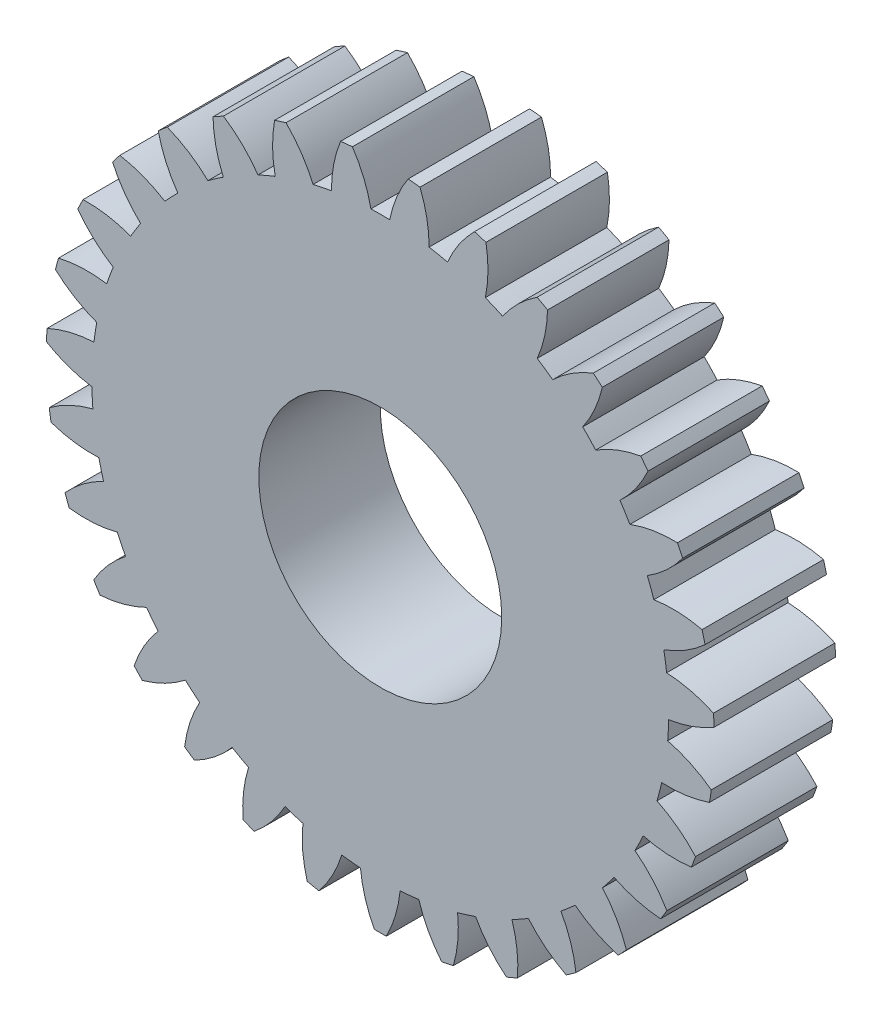
SolidWorks part; units mm, degrees
ref_plane "前视基准面" through (0, 0, 0) normal (0, 0, 1) x (1, 0, 0)
ref_plane "上视基准面" through (0, 0, 0) normal (0, 1, 0) x (1, 0, 0)
ref_plane "右视基准面" through (0, 0, 0) normal (1, 0, 0) x (0, 0, -1)
sketch "草图1" plane through (0, 0, 0) normal (0, 0, 1) x (1, 0, 0)
  circle A0 centre (0, 0) radius 3 construction
  circle A1 centre (0, 0) radius 3
  arc A124 (7.1228, -0.129) -> (8.2456, 0.2706) centre (6.6642, 2.9369) ccw
  arc A125 (8.2456, 0.2706) -> (8.2306, 0.565) centre (0, 0) ccw
  arc A126 (8.2306, 0.565) -> (7.0732, 0.8489) centre (6.9271, -2.2477) ccw
  arc A127 (7.0732, 0.8489) -> (7.003, 1.3075) centre (0, 0) ccw
  arc A128 (7.003, 1.3075) -> (8.0223, 1.9249) centre (5.9365, 4.2183) ccw
  arc A129 (8.0223, 1.9249) -> (7.9484, 2.2102) centre (0, 0) ccw
  arc A130 (7.9484, 2.2102) -> (6.7576, 2.2554) centre (7.2377, -0.8072) ccw
  arc A131 (6.7576, 2.2554) -> (6.5964, 2.6904) centre (0, 0) ccw
  arc A132 (6.5964, 2.6904) -> (7.4706, 3.5004) centre (4.9659, 5.327) ccw
  arc A133 (7.4706, 3.5004) -> (7.3408, 3.765) centre (0, 0) ccw
  arc A134 (7.3408, 3.765) -> (6.1652, 3.5695) centre (7.2521, 0.6662) ccw
  arc A135 (6.1652, 3.5695) -> (5.9198, 3.9632) centre (0, 0) ccw
  arc A136 (5.9198, 3.9632) -> (6.6131, 4.9325) centre (3.7919, 6.2175) ccw
  arc A137 (6.6131, 4.9325) -> (6.4327, 5.1656) centre (0, 0) ccw
  arc A138 (6.4327, 5.1656) -> (5.3205, 4.7375) centre (6.9695, 2.1124) ccw
  arc A139 (5.3205, 4.7375) -> (5.0009, 5.0737) centre (0, 0) ccw
  arc A140 (5.0009, 5.0737) -> (5.4848, 6.1628) centre (2.4627, 6.8536) ccw
  arc A141 (5.4848, 6.1628) -> (5.2612, 6.3547) centre (0, 0) ccw
  arc A142 (5.2612, 6.3547) -> (4.258, 5.7115) centre (6.4016, 3.4721) ccw
  arc A143 (4.258, 5.7115) -> (3.8772, 5.9765) centre (0, 0) ccw
  arc A144 (3.8772, 5.9765) -> (4.1319, 7.1407) centre (1.0327, 7.209) ccw
  arc A145 (4.1319, 7.1407) -> (3.8743, 7.2837) centre (0, 0) ccw
  arc A146 (3.8743, 7.2837) -> (3.0211, 6.4517) centre (5.5716, 4.6897) ccw
  arc A147 (3.0211, 6.4517) -> (2.5947, 6.6347) centre (0, 0) ccw
  arc A148 (2.5947, 6.6347) -> (2.6099, 7.8263) centre (-0.4396, 7.2693) ccw
  arc A149 (2.6099, 7.8263) -> (2.3288, 7.9145) centre (0, 0) ccw
  arc A150 (2.3288, 7.9145) -> (1.6605, 6.9278) centre (4.5136, 5.7153) ccw
  arc A151 (1.6605, 6.9278) -> (1.2061, 7.0212) centre (0, 0) ccw
  arc A152 (1.2061, 7.0212) -> (0.9811, 8.1915) centre (-1.8939, 7.032) ccw
  arc A153 (0.9811, 8.1915) -> (0.6879, 8.2213) centre (0, 0) ccw
  arc A154 (0.6879, 8.2213) -> (0.232, 7.1202) centre (3.2707, 6.5069) ccw
  arc A155 (0.232, 7.1202) -> (-0.232, 7.1202) centre (0, 0) ccw
  arc A156 (-0.232, 7.1202) -> (-0.6879, 8.2213) centre (-3.2707, 6.5069) ccw
  arc A157 (-0.6879, 8.2213) -> (-0.9811, 8.1915) centre (0, 0) ccw
  arc A158 (-0.9811, 8.1915) -> (-1.2061, 7.0212) centre (1.8939, 7.032) ccw
  arc A159 (-1.2061, 7.0212) -> (-1.6605, 6.9278) centre (0, 0) ccw
  arc A160 (-1.6605, 6.9278) -> (-2.3288, 7.9145) centre (-4.5136, 5.7153) ccw
  arc A161 (-2.3288, 7.9145) -> (-2.6099, 7.8263) centre (0, 0) ccw
  arc A162 (-2.6099, 7.8263) -> (-2.5947, 6.6347) centre (0.4396, 7.2693) ccw
  arc A163 (-2.5947, 6.6347) -> (-3.0211, 6.4517) centre (0, 0) ccw
  arc A164 (-3.0211, 6.4517) -> (-3.8743, 7.2837) centre (-5.5716, 4.6897) ccw
  arc A165 (-3.8743, 7.2837) -> (-4.1319, 7.1407) centre (0, 0) ccw
  arc A166 (-4.1319, 7.1407) -> (-3.8772, 5.9765) centre (-1.0327, 7.209) ccw
  arc A167 (-3.8772, 5.9765) -> (-4.258, 5.7115) centre (0, 0) ccw
  arc A168 (-4.258, 5.7115) -> (-5.2612, 6.3547) centre (-6.4016, 3.4721) ccw
  arc A169 (-5.2612, 6.3547) -> (-5.4848, 6.1628) centre (0, 0) ccw
  arc A170 (-5.4848, 6.1628) -> (-5.0009, 5.0737) centre (-2.4627, 6.8536) ccw
  arc A171 (-5.0009, 5.0737) -> (-5.3205, 4.7375) centre (0, 0) ccw
  arc A172 (-5.3205, 4.7375) -> (-6.4327, 5.1656) centre (-6.9695, 2.1124) ccw
  arc A173 (-6.4327, 5.1656) -> (-6.6131, 4.9325) centre (0, 0) ccw
  arc A174 (-6.6131, 4.9325) -> (-5.9198, 3.9632) centre (-3.7919, 6.2175) ccw
  arc A175 (-5.9198, 3.9632) -> (-6.1652, 3.5695) centre (0, 0) ccw
  arc A176 (-6.1652, 3.5695) -> (-7.3408, 3.765) centre (-7.2521, 0.6662) ccw
  arc A177 (-7.3408, 3.765) -> (-7.4706, 3.5004) centre (0, 0) ccw
  arc A178 (-7.4706, 3.5004) -> (-6.5964, 2.6904) centre (-4.9659, 5.327) ccw
  arc A179 (-6.5964, 2.6904) -> (-6.7576, 2.2554) centre (0, 0) ccw
  arc A180 (-6.7576, 2.2554) -> (-7.9484, 2.2102) centre (-7.2377, -0.8072) ccw
  arc A181 (-7.9484, 2.2102) -> (-8.0223, 1.9249) centre (0, 0) ccw
  arc A182 (-8.0223, 1.9249) -> (-7.003, 1.3075) centre (-5.9365, 4.2183) ccw
  arc A183 (-7.003, 1.3075) -> (-7.0732, 0.8489) centre (0, 0) ccw
  arc A184 (-7.0732, 0.8489) -> (-8.2306, 0.565) centre (-6.9271, -2.2477) ccw
  arc A185 (-8.2306, 0.565) -> (-8.2456, 0.2706) centre (0, 0) ccw
  arc A186 (-8.2456, 0.2706) -> (-7.1228, -0.129) centre (-6.6642, 2.9369) ccw
  arc A187 (-7.1228, -0.129) -> (-7.0993, -0.5923) centre (0, 0) ccw
  arc A188 (-7.0993, -0.5923) -> (-8.1759, -1.1034) centre (-6.3328, -3.5961) ccw
  arc A189 (-8.1759, -1.1034) -> (-8.1312, -1.3947) centre (0, 0) ccw
  arc A190 (-8.1312, -1.3947) -> (-6.9511, -1.5601) centre (-7.1189, 1.5353) ccw
  arc A191 (-6.9511, -1.5601) -> (-6.8348, -2.0093) centre (0, 0) ccw
  arc A192 (-6.8348, -2.0093) -> (-7.7864, -2.7266) centre (-5.4793, -4.7972) ccw
  arc A193 (-7.7864, -2.7266) -> (-7.684, -3.003) centre (0, 0) ccw
  arc A194 (-7.684, -3.003) -> (-6.4947, -2.9274) centre (-7.2823, 0.0709) ccw
  arc A195 (-6.4947, -2.9274) -> (-6.2904, -3.344) centre (0, 0) ccw
  arc A196 (-6.2904, -3.344) -> (-7.0781, -4.2382) centre (-4.4015, -5.802) ccw
  arc A197 (-7.0781, -4.2382) -> (-6.9223, -4.4883) centre (0, 0) ccw
  arc A198 (-6.9223, -4.4883) -> (-5.7725, -4.1749) centre (-7.1475, -1.3965) ccw
  arc A199 (-5.7725, -4.1749) -> (-5.4885, -4.5418) centre (0, 0) ccw
  arc A200 (-5.4885, -4.5418) -> (-6.0801, -5.5763) centre (-3.1435, -6.5693) ccw
  arc A201 (-6.0801, -5.5763) -> (-5.8771, -5.7899) centre (0, 0) ccw
  arc A202 (-5.8771, -5.7899) -> (-4.8139, -5.2514) centre (-6.72, -2.8067) ccw
  arc A203 (-4.8139, -5.2514) -> (-4.4619, -5.5536) centre (0, 0) ccw
  arc A204 (-4.4619, -5.5536) -> (-4.8332, -6.686) centre (-1.7567, -7.0676) ccw
  arc A205 (-4.8332, -6.686) -> (-4.5913, -6.8544) centre (0, 0) ccw
  arc A206 (-4.5913, -6.8544) -> (-3.6583, -6.113) centre (-6.0175, -4.102) ccw
  arc A207 (-3.6583, -6.113) -> (-3.2526, -6.3381) centre (0, 0) ccw
  arc A208 (-3.2526, -6.3381) -> (-3.3883, -7.5221) centre (-0.2981, -7.2765) ccw
  arc A209 (-3.3883, -7.5221) -> (-3.1175, -7.6383) centre (0, 0) ccw
  arc A210 (-3.1175, -7.6383) -> (-2.3529, -6.7242) centre (-5.0686, -5.2293) ccw
  arc A211 (-2.3529, -6.7242) -> (-1.9102, -6.8631) centre (0, 0) ccw
  arc A212 (-1.9102, -6.8631) -> (-1.8048, -8.0502) centre (1.1728, -7.1876) ccw
  arc A213 (-1.8048, -8.0502) -> (-1.5161, -8.1095) centre (0, 0) ccw
  arc A214 (-1.5161, -8.1095) -> (-0.9511, -7.0602) centre (-3.9122, -6.1426) ccw
  arc A215 (-0.9511, -7.0602) -> (-0.4896, -7.1072) centre (0, 0) ccw
  arc A216 (-0.4896, -7.1072) -> (-0.1474, -8.2487) centre (2.5956, -6.8044) ccw
  arc A217 (-0.1474, -8.2487) -> (0.1474, -8.2487) centre (0, 0) ccw
  arc A218 (0.1474, -8.2487) -> (0.4896, -7.1072) centre (-2.5956, -6.8044) ccw
  arc A219 (0.4896, -7.1072) -> (0.9511, -7.0602) centre (0, 0) ccw
  arc A220 (0.9511, -7.0602) -> (1.5161, -8.1095) centre (3.9122, -6.1426) ccw
  arc A221 (1.5161, -8.1095) -> (1.8048, -8.0502) centre (0, 0) ccw
  arc A222 (1.8048, -8.0502) -> (1.9102, -6.8631) centre (-1.1728, -7.1876) ccw
  arc A223 (1.9102, -6.8631) -> (2.3529, -6.7242) centre (0, 0) ccw
  arc A224 (2.3529, -6.7242) -> (3.1175, -7.6383) centre (5.0686, -5.2293) ccw
  arc A225 (3.1175, -7.6383) -> (3.3883, -7.5221) centre (0, 0) ccw
  arc A226 (3.3883, -7.5221) -> (3.2526, -6.3381) centre (0.2981, -7.2765) ccw
  arc A227 (3.2526, -6.3381) -> (3.6583, -6.113) centre (0, 0) ccw
  arc A228 (3.6583, -6.113) -> (4.5913, -6.8544) centre (6.0175, -4.102) ccw
  arc A229 (4.5913, -6.8544) -> (4.8332, -6.686) centre (0, 0) ccw
  arc A230 (4.8332, -6.686) -> (4.4619, -5.5536) centre (1.7567, -7.0676) ccw
  arc A231 (4.4619, -5.5536) -> (4.8139, -5.2514) centre (0, 0) ccw
  arc A232 (4.8139, -5.2514) -> (5.8771, -5.7899) centre (6.72, -2.8067) ccw
  arc A233 (5.8771, -5.7899) -> (6.0801, -5.5763) centre (0, 0) ccw
  arc A234 (6.0801, -5.5763) -> (5.4885, -4.5418) centre (3.1435, -6.5693) ccw
  arc A235 (5.4885, -4.5418) -> (5.7725, -4.1749) centre (0, 0) ccw
  arc A236 (5.7725, -4.1749) -> (6.9223, -4.4883) centre (7.1475, -1.3965) ccw
  arc A237 (6.9223, -4.4883) -> (7.0781, -4.2382) centre (0, 0) ccw
  arc A238 (7.0781, -4.2382) -> (6.2904, -3.344) centre (4.4015, -5.802) ccw
  arc A239 (6.2904, -3.344) -> (6.4947, -2.9274) centre (0, 0) ccw
  arc A240 (6.4947, -2.9274) -> (7.684, -3.003) centre (7.2823, 0.0709) ccw
  arc A241 (7.684, -3.003) -> (7.7864, -2.7266) centre (0, 0) ccw
  arc A242 (7.7864, -2.7266) -> (6.8348, -2.0093) centre (5.4793, -4.7972) ccw
  arc A243 (6.8348, -2.0093) -> (6.9511, -1.5601) centre (0, 0) ccw
  arc A244 (6.9511, -1.5601) -> (8.1312, -1.3947) centre (7.1189, 1.5353) ccw
  arc A245 (8.1312, -1.3947) -> (8.1759, -1.1034) centre (0, 0) ccw
  arc A246 (8.1759, -1.1034) -> (7.0993, -0.5923) centre (6.3328, -3.5961) ccw
  arc A247 (7.0993, -0.5923) -> (7.1228, -0.129) centre (0, 0) ccw
  arc A248 (7.1228, -0.129) -> (8.2456, 0.2706) centre (6.6642, 2.9369) ccw
  arc A249 (8.2456, 0.2706) -> (8.2306, 0.565) centre (0, 0) ccw
  arc A250 (8.2306, 0.565) -> (7.0732, 0.8489) centre (6.9271, -2.2477) ccw
  arc A251 (7.0732, 0.8489) -> (7.003, 1.3075) centre (0, 0) ccw
  arc A252 (7.003, 1.3075) -> (8.0223, 1.9249) centre (5.9365, 4.2183) ccw
  arc A253 (8.0223, 1.9249) -> (7.9484, 2.2102) centre (0, 0) ccw
  arc A254 (7.9484, 2.2102) -> (6.7576, 2.2554) centre (7.2377, -0.8072) ccw
  arc A255 (6.7576, 2.2554) -> (6.5964, 2.6904) centre (0, 0) ccw
  arc A256 (6.5964, 2.6904) -> (7.4706, 3.5004) centre (4.9659, 5.327) ccw
  arc A257 (7.4706, 3.5004) -> (7.3408, 3.765) centre (0, 0) ccw
  arc A258 (7.3408, 3.765) -> (6.1652, 3.5695) centre (7.2521, 0.6662) ccw
  arc A259 (6.1652, 3.5695) -> (5.9198, 3.9632) centre (0, 0) ccw
  arc A260 (5.9198, 3.9632) -> (6.6131, 4.9325) centre (3.7919, 6.2175) ccw
  arc A261 (6.6131, 4.9325) -> (6.4327, 5.1656) centre (0, 0) ccw
  arc A262 (6.4327, 5.1656) -> (5.3205, 4.7375) centre (6.9695, 2.1124) ccw
  arc A263 (5.3205, 4.7375) -> (5.0009, 5.0737) centre (0, 0) ccw
  arc A264 (5.0009, 5.0737) -> (5.4848, 6.1628) centre (2.4627, 6.8536) ccw
  arc A265 (5.4848, 6.1628) -> (5.2612, 6.3547) centre (0, 0) ccw
  arc A266 (5.2612, 6.3547) -> (4.258, 5.7115) centre (6.4016, 3.4721) ccw
  arc A267 (4.258, 5.7115) -> (3.8772, 5.9765) centre (0, 0) ccw
  arc A268 (3.8772, 5.9765) -> (4.1319, 7.1407) centre (1.0327, 7.209) ccw
  arc A269 (4.1319, 7.1407) -> (3.8743, 7.2837) centre (0, 0) ccw
  arc A270 (3.8743, 7.2837) -> (3.0211, 6.4517) centre (5.5716, 4.6897) ccw
  arc A271 (3.0211, 6.4517) -> (2.5947, 6.6347) centre (0, 0) ccw
  arc A272 (2.5947, 6.6347) -> (2.6099, 7.8263) centre (-0.4396, 7.2693) ccw
  arc A273 (2.6099, 7.8263) -> (2.3288, 7.9145) centre (0, 0) ccw
  arc A274 (2.3288, 7.9145) -> (1.6605, 6.9278) centre (4.5136, 5.7153) ccw
  arc A275 (1.6605, 6.9278) -> (1.2061, 7.0212) centre (0, 0) ccw
  arc A276 (1.2061, 7.0212) -> (0.9811, 8.1915) centre (-1.8939, 7.032) ccw
  arc A277 (0.9811, 8.1915) -> (0.6879, 8.2213) centre (0, 0) ccw
  arc A278 (0.6879, 8.2213) -> (0.232, 7.1202) centre (3.2707, 6.5069) ccw
  arc A279 (0.232, 7.1202) -> (-0.232, 7.1202) centre (0, 0) ccw
  arc A280 (-0.232, 7.1202) -> (-0.6879, 8.2213) centre (-3.2707, 6.5069) ccw
  arc A281 (-0.6879, 8.2213) -> (-0.9811, 8.1915) centre (0, 0) ccw
  arc A282 (-0.9811, 8.1915) -> (-1.2061, 7.0212) centre (1.8939, 7.032) ccw
  arc A283 (-1.2061, 7.0212) -> (-1.6605, 6.9278) centre (0, 0) ccw
  arc A284 (-1.6605, 6.9278) -> (-2.3288, 7.9145) centre (-4.5136, 5.7153) ccw
  arc A285 (-2.3288, 7.9145) -> (-2.6099, 7.8263) centre (0, 0) ccw
  arc A286 (-2.6099, 7.8263) -> (-2.5947, 6.6347) centre (0.4396, 7.2693) ccw
  arc A287 (-2.5947, 6.6347) -> (-3.0211, 6.4517) centre (0, 0) ccw
  arc A288 (-3.0211, 6.4517) -> (-3.8743, 7.2837) centre (-5.5716, 4.6897) ccw
  arc A289 (-3.8743, 7.2837) -> (-4.1319, 7.1407) centre (0, 0) ccw
  arc A290 (-4.1319, 7.1407) -> (-3.8772, 5.9765) centre (-1.0327, 7.209) ccw
  arc A291 (-3.8772, 5.9765) -> (-4.258, 5.7115) centre (0, 0) ccw
  arc A292 (-4.258, 5.7115) -> (-5.2612, 6.3547) centre (-6.4016, 3.4721) ccw
  arc A293 (-5.2612, 6.3547) -> (-5.4848, 6.1628) centre (0, 0) ccw
  arc A294 (-5.4848, 6.1628) -> (-5.0009, 5.0737) centre (-2.4627, 6.8536) ccw
  arc A295 (-5.0009, 5.0737) -> (-5.3205, 4.7375) centre (0, 0) ccw
  arc A296 (-5.3205, 4.7375) -> (-6.4327, 5.1656) centre (-6.9695, 2.1124) ccw
  arc A297 (-6.4327, 5.1656) -> (-6.6131, 4.9325) centre (0, 0) ccw
  arc A298 (-6.6131, 4.9325) -> (-5.9198, 3.9632) centre (-3.7919, 6.2175) ccw
  arc A299 (-5.9198, 3.9632) -> (-6.1652, 3.5695) centre (0, 0) ccw
  arc A300 (-6.1652, 3.5695) -> (-7.3408, 3.765) centre (-7.2521, 0.6662) ccw
  arc A301 (-7.3408, 3.765) -> (-7.4706, 3.5004) centre (0, 0) ccw
  arc A302 (-7.4706, 3.5004) -> (-6.5964, 2.6904) centre (-4.9659, 5.327) ccw
  arc A303 (-6.5964, 2.6904) -> (-6.7576, 2.2554) centre (0, 0) ccw
  arc A304 (-6.7576, 2.2554) -> (-7.9484, 2.2102) centre (-7.2377, -0.8072) ccw
  arc A305 (-7.9484, 2.2102) -> (-8.0223, 1.9249) centre (0, 0) ccw
  arc A306 (-8.0223, 1.9249) -> (-7.003, 1.3075) centre (-5.9365, 4.2183) ccw
  arc A307 (-7.003, 1.3075) -> (-7.0732, 0.8489) centre (0, 0) ccw
  arc A308 (-7.0732, 0.8489) -> (-8.2306, 0.565) centre (-6.9271, -2.2477) ccw
  arc A309 (-8.2306, 0.565) -> (-8.2456, 0.2706) centre (0, 0) ccw
  arc A310 (-8.2456, 0.2706) -> (-7.1228, -0.129) centre (-6.6642, 2.9369) ccw
  arc A311 (-7.1228, -0.129) -> (-7.0993, -0.5923) centre (0, 0) ccw
  arc A312 (-7.0993, -0.5923) -> (-8.1759, -1.1034) centre (-6.3328, -3.5961) ccw
  arc A313 (-8.1759, -1.1034) -> (-8.1312, -1.3947) centre (0, 0) ccw
  arc A314 (-8.1312, -1.3947) -> (-6.9511, -1.5601) centre (-7.1189, 1.5353) ccw
  arc A315 (-6.9511, -1.5601) -> (-6.8348, -2.0093) centre (0, 0) ccw
  arc A316 (-6.8348, -2.0093) -> (-7.7864, -2.7266) centre (-5.4793, -4.7972) ccw
  arc A317 (-7.7864, -2.7266) -> (-7.684, -3.003) centre (0, 0) ccw
  arc A318 (-7.684, -3.003) -> (-6.4947, -2.9274) centre (-7.2823, 0.0709) ccw
  arc A319 (-6.4947, -2.9274) -> (-6.2904, -3.344) centre (0, 0) ccw
  arc A320 (-6.2904, -3.344) -> (-7.0781, -4.2382) centre (-4.4015, -5.802) ccw
  arc A321 (-7.0781, -4.2382) -> (-6.9223, -4.4883) centre (0, 0) ccw
  arc A322 (-6.9223, -4.4883) -> (-5.7725, -4.1749) centre (-7.1475, -1.3965) ccw
  arc A323 (-5.7725, -4.1749) -> (-5.4885, -4.5418) centre (0, 0) ccw
  arc A324 (-5.4885, -4.5418) -> (-6.0801, -5.5763) centre (-3.1435, -6.5693) ccw
  arc A325 (-6.0801, -5.5763) -> (-5.8771, -5.7899) centre (0, 0) ccw
  arc A326 (-5.8771, -5.7899) -> (-4.8139, -5.2514) centre (-6.72, -2.8067) ccw
  arc A327 (-4.8139, -5.2514) -> (-4.4619, -5.5536) centre (0, 0) ccw
  arc A328 (-4.4619, -5.5536) -> (-4.8332, -6.686) centre (-1.7567, -7.0676) ccw
  arc A329 (-4.8332, -6.686) -> (-4.5913, -6.8544) centre (0, 0) ccw
  arc A330 (-4.5913, -6.8544) -> (-3.6583, -6.113) centre (-6.0175, -4.102) ccw
  arc A331 (-3.6583, -6.113) -> (-3.2526, -6.3381) centre (0, 0) ccw
  arc A332 (-3.2526, -6.3381) -> (-3.3883, -7.5221) centre (-0.2981, -7.2765) ccw
  arc A333 (-3.3883, -7.5221) -> (-3.1175, -7.6383) centre (0, 0) ccw
  arc A334 (-3.1175, -7.6383) -> (-2.3529, -6.7242) centre (-5.0686, -5.2293) ccw
  arc A335 (-2.3529, -6.7242) -> (-1.9102, -6.8631) centre (0, 0) ccw
  arc A336 (-1.9102, -6.8631) -> (-1.8048, -8.0502) centre (1.1728, -7.1876) ccw
  arc A337 (-1.8048, -8.0502) -> (-1.5161, -8.1095) centre (0, 0) ccw
  arc A338 (-1.5161, -8.1095) -> (-0.9511, -7.0602) centre (-3.9122, -6.1426) ccw
  arc A339 (-0.9511, -7.0602) -> (-0.4896, -7.1072) centre (0, 0) ccw
  arc A340 (-0.4896, -7.1072) -> (-0.1474, -8.2487) centre (2.5956, -6.8044) ccw
  arc A341 (-0.1474, -8.2487) -> (0.1474, -8.2487) centre (0, 0) ccw
  arc A342 (0.1474, -8.2487) -> (0.4896, -7.1072) centre (-2.5956, -6.8044) ccw
  arc A343 (0.4896, -7.1072) -> (0.9511, -7.0602) centre (0, 0) ccw
  arc A344 (0.9511, -7.0602) -> (1.5161, -8.1095) centre (3.9122, -6.1426) ccw
  arc A345 (1.5161, -8.1095) -> (1.8048, -8.0502) centre (0, 0) ccw
  arc A346 (1.8048, -8.0502) -> (1.9102, -6.8631) centre (-1.1728, -7.1876) ccw
  arc A347 (1.9102, -6.8631) -> (2.3529, -6.7242) centre (0, 0) ccw
  arc A348 (2.3529, -6.7242) -> (3.1175, -7.6383) centre (5.0686, -5.2293) ccw
  arc A349 (3.1175, -7.6383) -> (3.3883, -7.5221) centre (0, 0) ccw
  arc A350 (3.3883, -7.5221) -> (3.2526, -6.3381) centre (0.2981, -7.2765) ccw
  arc A351 (3.2526, -6.3381) -> (3.6583, -6.113) centre (0, 0) ccw
  arc A352 (3.6583, -6.113) -> (4.5913, -6.8544) centre (6.0175, -4.102) ccw
  arc A353 (4.5913, -6.8544) -> (4.8332, -6.686) centre (0, 0) ccw
  arc A354 (4.8332, -6.686) -> (4.4619, -5.5536) centre (1.7567, -7.0676) ccw
  arc A355 (4.4619, -5.5536) -> (4.8139, -5.2514) centre (0, 0) ccw
  arc A356 (4.8139, -5.2514) -> (5.8771, -5.7899) centre (6.72, -2.8067) ccw
  arc A357 (5.8771, -5.7899) -> (6.0801, -5.5763) centre (0, 0) ccw
  arc A358 (6.0801, -5.5763) -> (5.4885, -4.5418) centre (3.1435, -6.5693) ccw
  arc A359 (5.4885, -4.5418) -> (5.7725, -4.1749) centre (0, 0) ccw
  arc A360 (5.7725, -4.1749) -> (6.9223, -4.4883) centre (7.1475, -1.3965) ccw
  arc A361 (6.9223, -4.4883) -> (7.0781, -4.2382) centre (0, 0) ccw
  arc A362 (7.0781, -4.2382) -> (6.2904, -3.344) centre (4.4015, -5.802) ccw
  arc A363 (6.2904, -3.344) -> (6.4947, -2.9274) centre (0, 0) ccw
  arc A364 (6.4947, -2.9274) -> (7.684, -3.003) centre (7.2823, 0.0709) ccw
  arc A365 (7.684, -3.003) -> (7.7864, -2.7266) centre (0, 0) ccw
  arc A366 (7.7864, -2.7266) -> (6.8348, -2.0093) centre (5.4793, -4.7972) ccw
  arc A367 (6.8348, -2.0093) -> (6.9511, -1.5601) centre (0, 0) ccw
  arc A368 (6.9511, -1.5601) -> (8.1312, -1.3947) centre (7.1189, 1.5353) ccw
  arc A369 (8.1312, -1.3947) -> (8.1759, -1.1034) centre (0, 0) ccw
  arc A370 (8.1759, -1.1034) -> (7.0993, -0.5923) centre (6.3328, -3.5961) ccw
  arc A371 (7.0993, -0.5923) -> (7.1228, -0.129) centre (0, 0) ccw
  dimension "D1" = 0
extrude "凸台-拉伸1" add sketch "草图1" along normal blind 3
